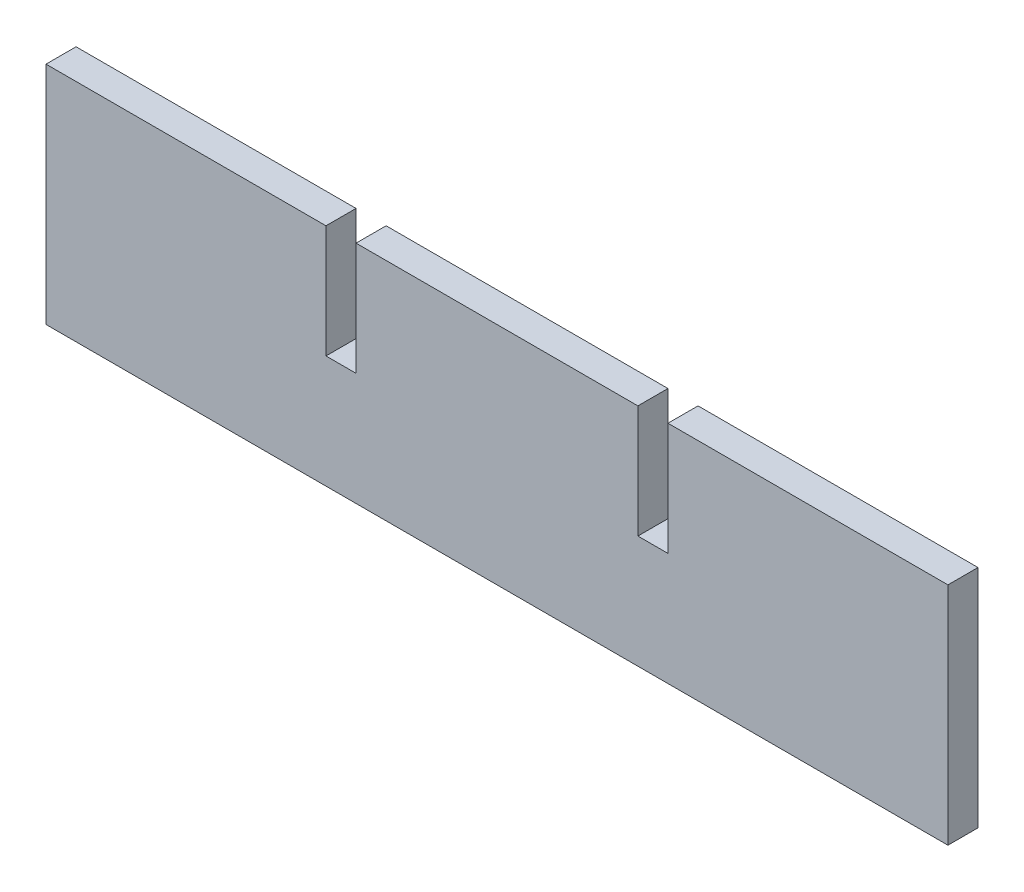
SolidWorks part; units mm, degrees
ref_plane "Plan de face" through (0, 0, 0) normal (0, 0, 1) x (1, 0, 0)
ref_plane "Plan de dessus" through (0, 0, 0) normal (0, 1, 0) x (1, 0, 0)
ref_plane "Plan de droite" through (0, 0, 0) normal (1, 0, 0) x (0, 0, -1)
sketch "Esquisse1" plane through (0, 0, 0) normal (0, 0, 1) x (1, 0, 0)
  line L0 (0, 0) -> (0, 60) construction
  line L1 (120, 0) -> (-120, 0)
  line L2 (-120, 0) -> (-120, 60)
  line L3 (-120, 60) -> (-45.5, 60)
  line L4 (-45.5, 60) -> (-45.5, 30)
  line L5 (-45.5, 30) -> (-37.5, 30)
  line L6 (-37.5, 30) -> (-37.5, 60)
  line L7 (-37.5, 60) -> (37.5, 60)
  line L8 (-41.5, 30) -> (-41.5, 0) construction
  line L9 (41.5, 30) -> (41.5, 0) construction
  line L10 (37.5, 30) -> (37.5, 60)
  line L11 (45.5, 30) -> (37.5, 30)
  line L12 (45.5, 60) -> (45.5, 30)
  line L13 (120, 60) -> (45.5, 60)
  line L14 (120, 0) -> (120, 60)
  dimension "D1" = 8
  dimension "D2" = 60
  dimension "D3" = 30
  dimension "D4" = 78.5
  dimension "D5" = 41.5
extrude "Boss.-Extru.1" add sketch "Esquisse1" along normal blind 8
